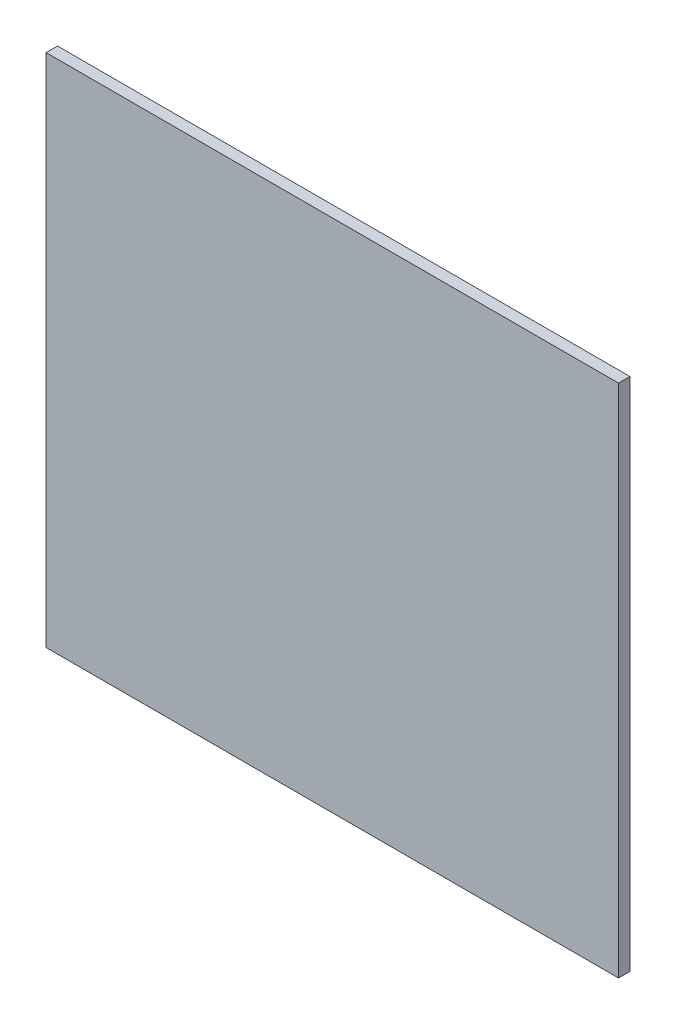
SolidWorks part; units mm, degrees
material "Plain Carbon Steel"
ref_plane "Front Plane" through (0, 0, 0) normal (0, 0, 1) x (1, 0, 0)
ref_plane "Top Plane" through (0, 0, 0) normal (0, 1, 0) x (1, 0, 0)
ref_plane "Right Plane" through (0, 0, 0) normal (1, 0, 0) x (0, 0, -1)
sketch "Sketch1" plane through (0, 0, 0) normal (0, 0, 1) x (1, 0, 0)
  line L1 (-100, -90) -> (100, -90)
  line L2 (-100, -90) -> (-100, 90)
  line L3 (-100, 90) -> (100, 90)
  line L4 (100, -90) -> (100, 90)
  line L5 (-100, -90) -> (100, 90) construction
  line L6 (-100, 90) -> (100, -90) construction
  point P0 (0, 0)
  dimension "D1" = 200
  dimension "D2" = 180
extrude "Boss-Extrude1" add sketch "Sketch1" along normal blind 4
